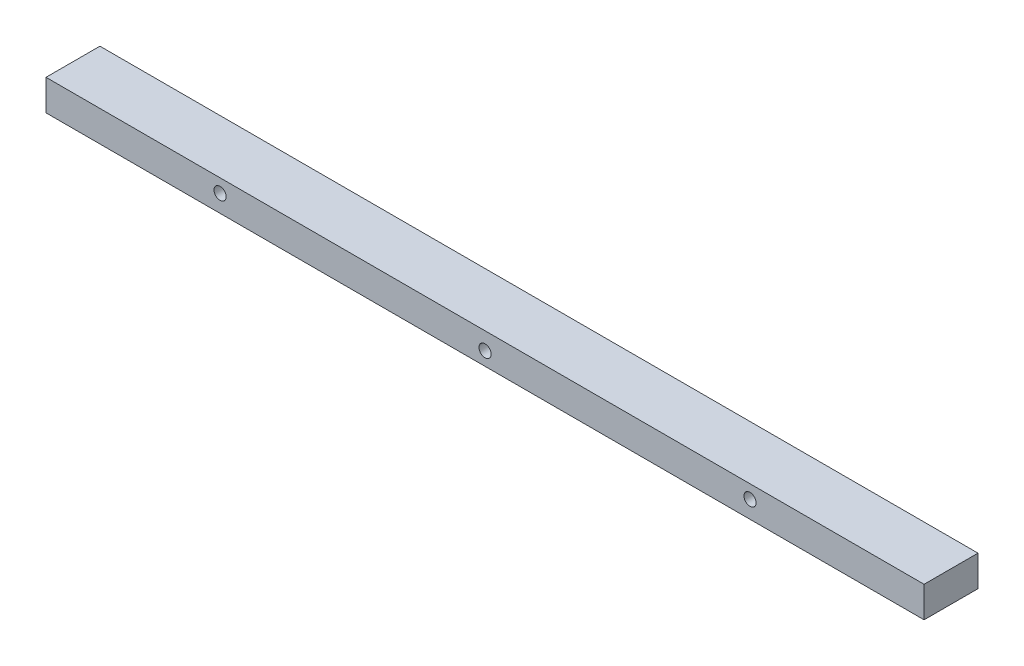
SolidWorks part; units mm, degrees
material "Polyethylene Cross-Linked"
ref_plane "Front Plane" through (0, 0, 0) normal (0, 0, 1) x (1, 0, 0)
ref_plane "Top Plane" through (0, 0, 0) normal (0, 1, 0) x (1, 0, 0)
ref_plane "Right Plane" through (0, 0, 0) normal (1, 0, 0) x (0, 0, -1)
sketch "Sketch1" plane through (0, 0, 0) normal (0, 0, 1) x (1, 0, 0)
  line L0 (180.975, 12.7) -> (180.975, 7.1437) construction
  line L1 (0, 0) -> (361.95, 0)
  line L2 (0, 0) -> (0, 12.7)
  line L3 (0, 12.7) -> (361.95, 12.7)
  line L4 (361.95, 0) -> (361.95, 12.7)
  line L5 (180.975, 7.1437) -> (180.975, 5.5563) construction
  line L6 (71.755, 7.1437) -> (290.195, 7.1438) construction
  circle A1 centre (180.975, 5.5563) radius 2.5
  circle A2 centre (71.755, 7.1437) radius 2.5
  circle A3 centre (290.195, 7.1438) radius 2.5
  point P12 (180.975, 7.1437)
  dimension "D5" = 218.44
  dimension "D1" = 12.7
  dimension "D2" = 361.95
  dimension "D3" = 5.5562
  dimension "D4" = 1.5875
extrude "Boss-Extrude1" add sketch "Sketch1" along normal blind 22.225
